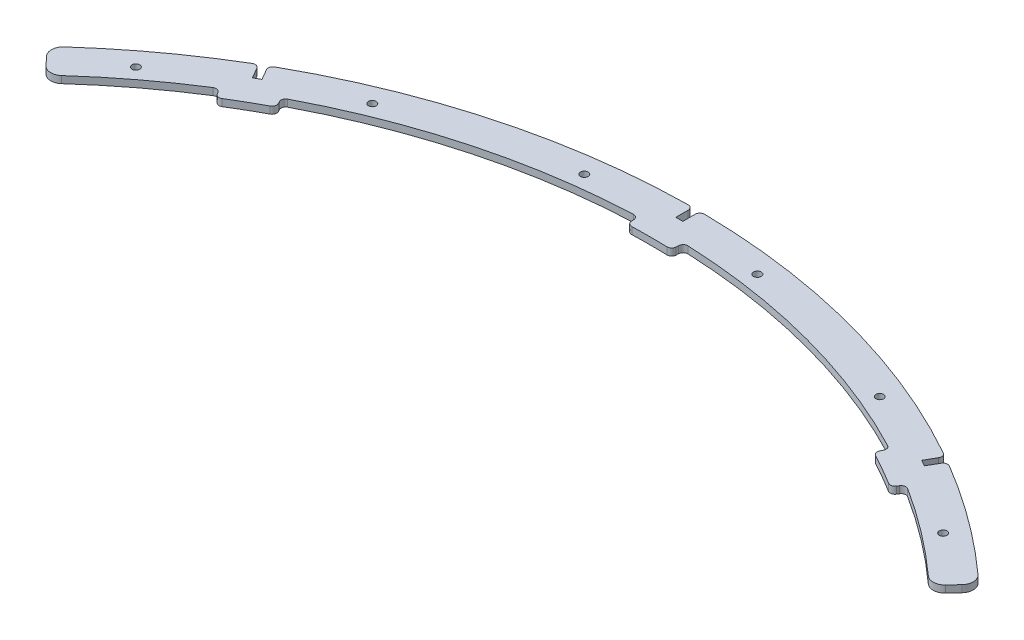
SolidWorks part; units mm, degrees
ref_plane "Front Plane" through (0, 0, 0) normal (0, 0, 1) x (1, 0, 0)
ref_plane "Top Plane" through (0, 0, 0) normal (0, 1, 0) x (1, 0, 0)
ref_plane "Right Plane" through (0, 0, 0) normal (1, 0, 0) x (0, 0, -1)
sketch "Sketch1" plane through (0, 0, 0) normal (0, 1, 0) x (1, 0, 0)
  line L0 (0, 0) -> (0, 291.5) construction
  line L1 (-145.75, 252.4464) -> (0, 0) construction
  line L2 (0, 0) -> (145.75, 252.4464) construction
  line L3 (-147.0471, 251.6931) -> (-143.399, 245.3744)
  line L4 (-143.399, 245.3744) -> (-140.801, 246.8744)
  line L5 (-140.801, 246.8744) -> (-144.449, 253.1931)
  line L6 (-1.5, 291.4961) -> (-1.5, 284.2)
  line L7 (1.5, 284.2) -> (1.5, 291.4961)
  line L8 (-1.5, 284.2) -> (1.5, 284.2)
  line L9 (144.449, 253.1931) -> (140.801, 246.8744)
  line L10 (143.399, 245.3744) -> (147.0471, 251.6931)
  line L11 (140.801, 246.8744) -> (143.399, 245.3744)
  line L12 (-154.4715, 247.206) -> (-143.8731, 230.2451)
  line L13 (-127.4615, 239.7203) -> (-129.8089, 244.135)
  line L14 (154.4715, 247.206) -> (143.8731, 230.2451)
  line L15 (127.4615, 239.7203) -> (129.8089, 244.135)
  line L16 (9.4752, 271.3346) -> (9.6497, 276.3316)
  line L17 (-9.6497, 276.3316) -> (-9.4752, 271.3346)
  circle A0 centre (0, 0) radius 291.5 construction
  circle A1 centre (0, 0) radius 284.5 construction
  arc A2 (1.5, 291.4961) -> (144.449, 253.1931) centre (0, 0) cw
  arc A3 (-144.449, 253.1931) -> (-1.5, 291.4961) centre (0, 0) cw
  arc A4 (-129.8089, 244.135) -> (-9.6497, 276.3316) centre (0, 0) cw
  arc A5 (-147.0471, 251.6931) -> (-154.4715, 247.206) centre (0, 0) ccw
  arc A6 (147.0471, 251.6931) -> (154.4715, 247.206) centre (0, 0) cw
  arc A7 (-143.8731, 230.2451) -> (-127.4615, 239.7203) centre (0, 0) cw
  arc A8 (143.8731, 230.2451) -> (127.4615, 239.7203) centre (0, 0) ccw
  arc A9 (-9.4752, 271.3346) -> (9.4752, 271.3346) centre (0, 0) cw
  arc A10 (9.6497, 276.3316) -> (129.8089, 244.135) centre (0, 0) cw
  point P12 (-142.25, 246.3842)
  point P23 (0, 0)
  point P41 (0, 0)
  dimension "D1" = 583
  dimension "D2" = 569
  dimension "D3" = 30
  dimension "D4" = 30
  dimension "D5" = 0.3
  dimension "D6" = 1.5
  dimension "D7" = 1.5
  dimension "D9" = 15
  dimension "D10" = 2
  dimension "D11" = 20
  dimension "D12" = 2
  dimension "D8" = 3
  dimension "D13" = 2
extrude "Boss-Extrude1" add sketch "Sketch1" along normal blind 3
fillet "Fillet1" radius 2 8 edges at (127.4615, 1.5, -239.7203) (129.8089, 1.5, -244.135) (-127.4615, 1.5, -239.7203) (-129.8089, 1.5, -244.135) (-9.6497, 1.5, -276.3316) (-9.4752, 1.5, -271.3346) (9.4752, 1.5, -271.3346) (9.6497, 1.5, -276.3316)
fillet "Fillet2" radius 2 4 edges at (-154.4715, 1.5, -247.206) (-143.8731, 1.5, -230.2451) (154.4715, 1.5, -247.206) (143.8731, 1.5, -230.2451)
fillet "Fillet3" radius 2 6 edges at (147.0471, 1.5, -251.6931) (144.449, 1.5, -253.1931) (-1.5, 1.5, -291.4961) (1.5, 1.5, -291.4961) (-144.449, 1.5, -253.1931) (-147.0471, 1.5, -251.6931)
sketch "Sketch2" plane through (0, 3, 0) normal (0, 1, 0) x (1, 0, 0)
  line L0 (-152.76, 248.2673) -> (-146.5227, 234.4853)
  line L1 (-191.9523, 205.8436) -> (-195.3628, 209.5009)
  line L2 (-145.75, 252.4464) -> (0, 0) construction
  line L3 (-153.408, 245.5041) -> (-144.929, 231.935) construction
  line L4 (0, -1000) -> (0, 49000) construction
  line L5 (191.9523, 205.8436) -> (195.3628, 209.5009)
  line L6 (152.76, 248.2673) -> (146.5227, 234.4853)
  arc A0 (-152.76, 248.2673) -> (-195.0517, 216.6266) centre (0, 0) ccw
  circle A1 centre (0, 0) radius 291.5 construction
  arc A2 (-146.5227, 234.4853) -> (-184.951, 205.5368) centre (0, 0) ccw
  arc A3 (-9.6497, 276.3316) -> (-129.8089, 244.135) centre (0, 0) ccw construction
  arc A5 (-195.0517, 216.6266) -> (-195.3628, 209.5009) centre (-191.706, 212.9109) ccw
  arc A6 (-184.951, 205.5368) -> (-191.9523, 205.8436) centre (-188.2955, 209.2536) cw
  arc A7 (184.951, 205.5368) -> (191.9523, 205.8436) centre (188.2955, 209.2536) ccw
  arc A8 (195.0517, 216.6266) -> (195.3628, 209.5009) centre (191.706, 212.9109) cw
  arc A9 (146.5227, 234.4853) -> (184.951, 205.5368) centre (0, 0) cw
  arc A10 (152.76, 248.2673) -> (195.0517, 216.6266) centre (0, 0) cw
  dimension "D2" = 5
  dimension "D1" = 13
extrude "Boss-Extrude2" add sketch "Sketch2" against normal up to surface (3 mm away) up to face at (0, 0, -257.1281)
fillet "Fillet4" radius 2 2 edges at (-146.5227, 1.5, -234.4853) (146.5227, 1.5, -234.4853)
sketch "Sketch3" plane through (0, 3, 0) normal (0, 1, 0) x (1, 0, 0)
  line L0 (0, 0) -> (0, 283) construction
  line L1 (-36.9389, 280.5789) -> (0, 0) construction
  line L2 (0, 0) -> (36.9389, 280.5789) construction
  line L3 (0, 0) -> (108.2994, 261.4579) construction
  line L4 (0, 0) -> (-108.2994, 261.4579) construction
  line L5 (172.2795, 224.519) -> (0, 0) construction
  line L6 (0, 0) -> (-172.2795, 224.519) construction
  circle A0 centre (0, 0) radius 283 construction
  circle A1 centre (-36.9389, 280.5789) radius 1.65
  circle A2 centre (36.9389, 280.5789) radius 1.65
  circle A3 centre (108.2994, 261.4579) radius 1.65
  circle A4 centre (-108.2994, 261.4579) radius 1.65
  circle A5 centre (172.2795, 224.519) radius 1.65
  circle A6 centre (-172.2795, 224.519) radius 1.65
  dimension "D1" = 566
  dimension "D4" = 3.3
  dimension "D2" = 7.5
  dimension "D3" = 7.5
  dimension "D5" = 15
  dimension "D6" = 15
  dimension "D7" = 15
  dimension "D8" = 15
extrude "Cut-Extrude1" cut sketch "Sketch3" against normal blind 10
equation "\"D4@Sketch1\"=\"D3@Sketch1\""
equation "\"D7@Sketch1\"=\"D6@Sketch1\""
equation "\"D2@Sketch3\"=\"D3@Sketch3\""
